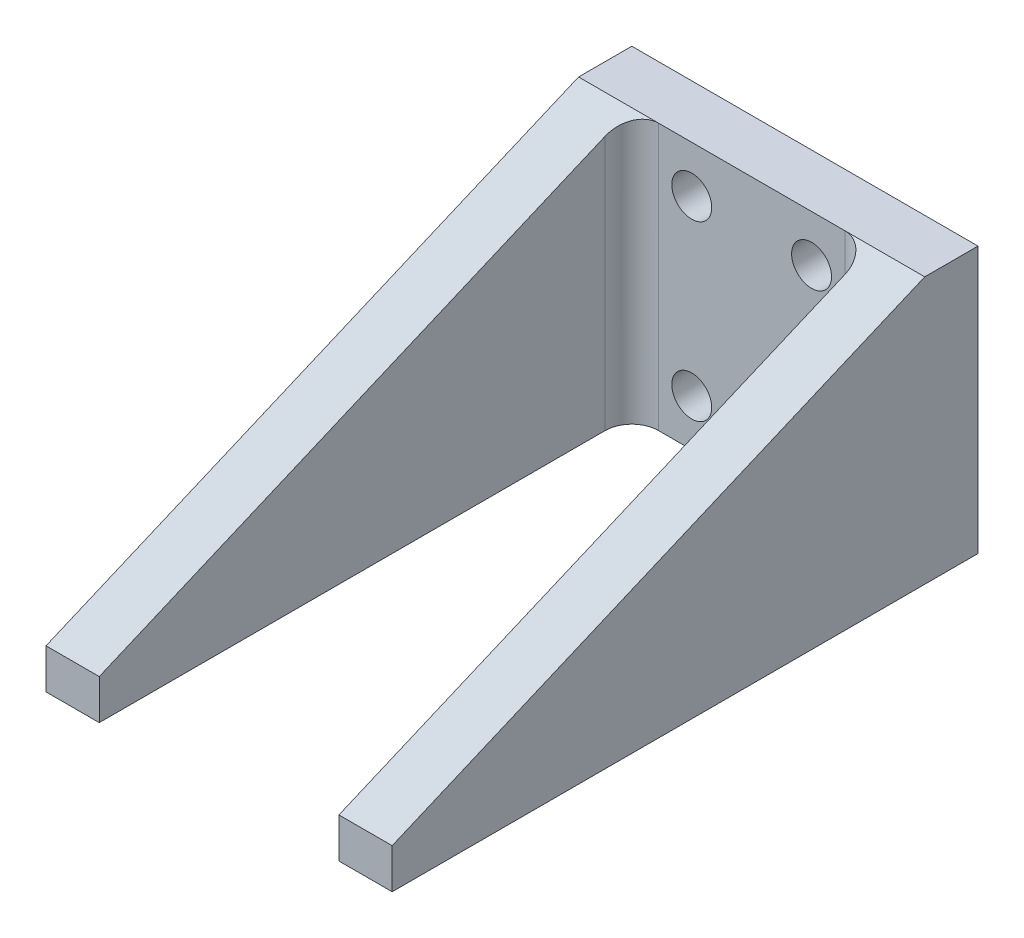
SolidWorks part; units mm, degrees
material "合金钢"
ref_plane "前视基准面" through (0, 0, 0) normal (0, 0, 1) x (1, 0, 0)
ref_plane "上视基准面" through (0, 0, 0) normal (0, 1, 0) x (1, 0, 0)
ref_plane "右视基准面" through (0, 0, 0) normal (1, 0, 0) x (0, 0, -1)
sketch "草图1" plane through (0, 0, 0) normal (0, 0, 1) x (1, 0, 0)
  line L1 (-13, -10) -> (13, -10)
  line L2 (-13, -10) -> (-13, 10)
  line L3 (-13, 10) -> (13, 10)
  line L4 (13, -10) -> (13, 10)
  line L5 (-13, -10) -> (13, 10) construction
  line L6 (-13, 10) -> (13, -10) construction
  point P0 (0, 0)
  dimension "D1" = 20
  dimension "D2" = 26
extrude "凸台-拉伸1" add sketch "草图1" along normal blind 4
sketch "草图2" plane through (0, 0, 4) normal (0, 0, 1) x (1, 0, 0)
  line L1 (-13, 10) -> (-9, 10)
  line L2 (-13, 10) -> (-13, -10)
  line L3 (-13, -10) -> (-9, -10)
  line L4 (-9, 10) -> (-9, -10)
  line L5 (-13, -10) -> (13, -10) construction
  line L7 (13, 10) -> (9, 10)
  line L8 (13, 10) -> (13, -10)
  line L9 (13, -10) -> (9, -10)
  line L10 (9, 10) -> (9, -10)
  dimension "D1" = 20
  dimension "D2" = 4
  dimension "D3" = 20
  dimension "D4" = 4
extrude "凸台-拉伸2" add sketch "草图2" along normal blind 40
sketch "草图3" plane through (0, 0, 4) normal (0, 0, 1) x (1, 0, 0)
  line L1 (-4.5, -6.5) -> (4.5, -6.5) construction
  line L2 (-4.5, -6.5) -> (-4.5, 6.5) construction
  line L3 (-4.5, 6.5) -> (4.5, 6.5) construction
  line L4 (4.5, -6.5) -> (4.5, 6.5) construction
  line L5 (-4.5, -6.5) -> (4.5, 6.5) construction
  line L6 (-4.5, 6.5) -> (4.5, -6.5) construction
  circle A0 centre (-4.5, 6.5) radius 1.5
  circle A1 centre (4.5, 6.5) radius 1.5
  circle A2 centre (4.5, -6.5) radius 1.5
  circle A3 centre (-4.5, -6.5) radius 1.5
  point P0 (0, 0)
  dimension "D3" = 3
  dimension "D4" = 3
  dimension "D5" = 3
  dimension "D6" = 3
  dimension "D1" = 13
  dimension "D2" = 9
extrude "切除-拉伸1" cut sketch "草图3" against normal blind 30
sketch "草图4" plane through (13, 0, 0) normal (1, 0, 0) x (0, 0, -1)
  line L0 (-44, -7) -> (-4, 10)
  line L1 (-44, 10) -> (0, 10) construction
  line L2 (-4, 10) -> (-44, 10)
  line L3 (-44, 10) -> (-44, -7)
  point P7 (-44, -7.2286)
  dimension "D1" = 4
  dimension "D2" = 3
extrude "切除-拉伸2" cut sketch "草图4" against normal through all
fillet "圆角1" radius 2 2 edges at (-9, 0, 4) (9, 0, 4)
